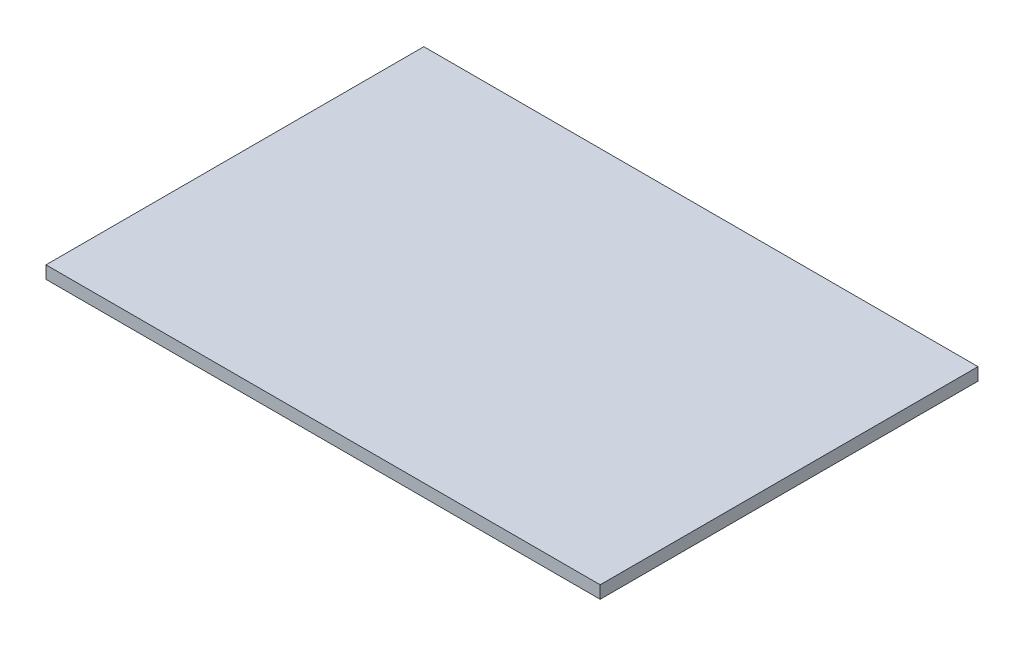
SolidWorks part; units mm, degrees
material "Thornel Mat VMA"
ref_plane "前视基准面" through (0, 0, 0) normal (0, 0, 1) x (1, 0, 0)
ref_plane "上视基准面" through (0, 0, 0) normal (0, 1, 0) x (1, 0, 0)
ref_plane "右视基准面" through (0, 0, 0) normal (1, 0, 0) x (0, 0, -1)
other "Configuration Table"
sketch "草图1" plane through (0, 0, 0) normal (0, 1, 0) x (1, 0, 0)
  line L1 (-88, -60) -> (88, -60)
  line L2 (-88, -60) -> (-88, 60)
  line L3 (-88, 60) -> (88, 60)
  line L4 (88, -60) -> (88, 60)
  line L5 (-88, -60) -> (88, 60) construction
  line L6 (-88, 60) -> (88, -60) construction
  point P0 (0, 0)
  dimension "D1" = 176
  dimension "D2" = 120
extrude "凸台-拉伸1" add sketch "草图1" along normal blind 4
